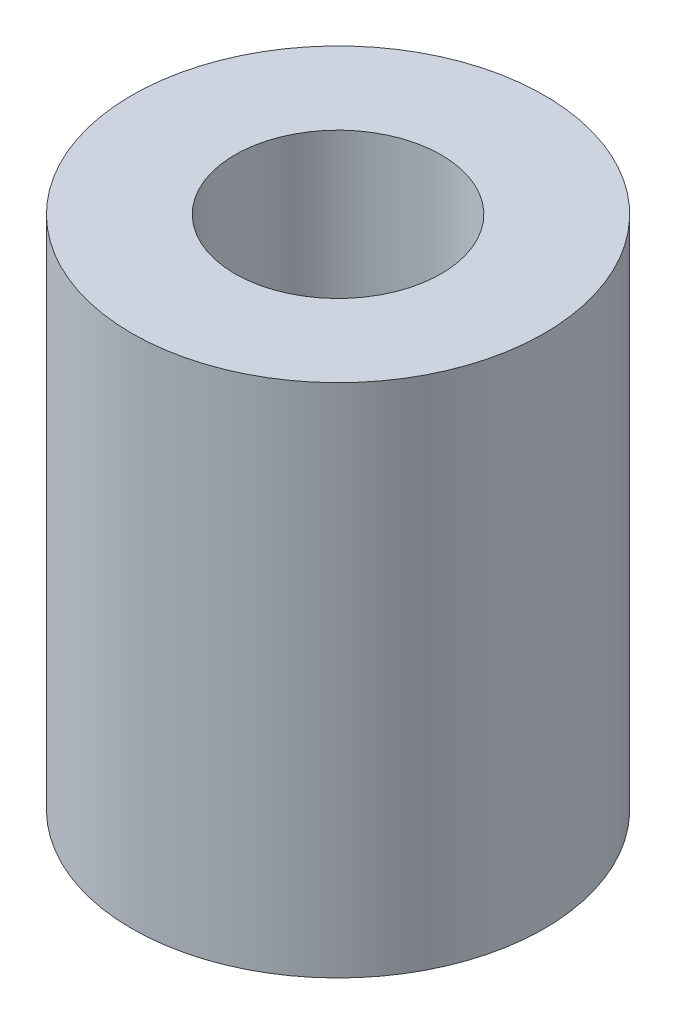
SolidWorks part; units mm, degrees
ref_plane "Front Plane" through (0, 0, 0) normal (0, 0, 1) x (1, 0, 0)
ref_plane "Top Plane" through (0, 0, 0) normal (0, 1, 0) x (1, 0, 0)
ref_plane "Right Plane" through (0, 0, 0) normal (1, 0, 0) x (0, 0, -1)
sketch "Sketch1" plane through (0, 0, 0) normal (0, 1, 0) x (1, 0, 0)
  circle A0 centre (0, 0) radius 10
  circle A1 centre (0, 0) radius 5
  dimension "D1" = 10
  dimension "D2" = 5
extrude "Boss-Extrude1" add sketch "Sketch1" along normal blind 25
